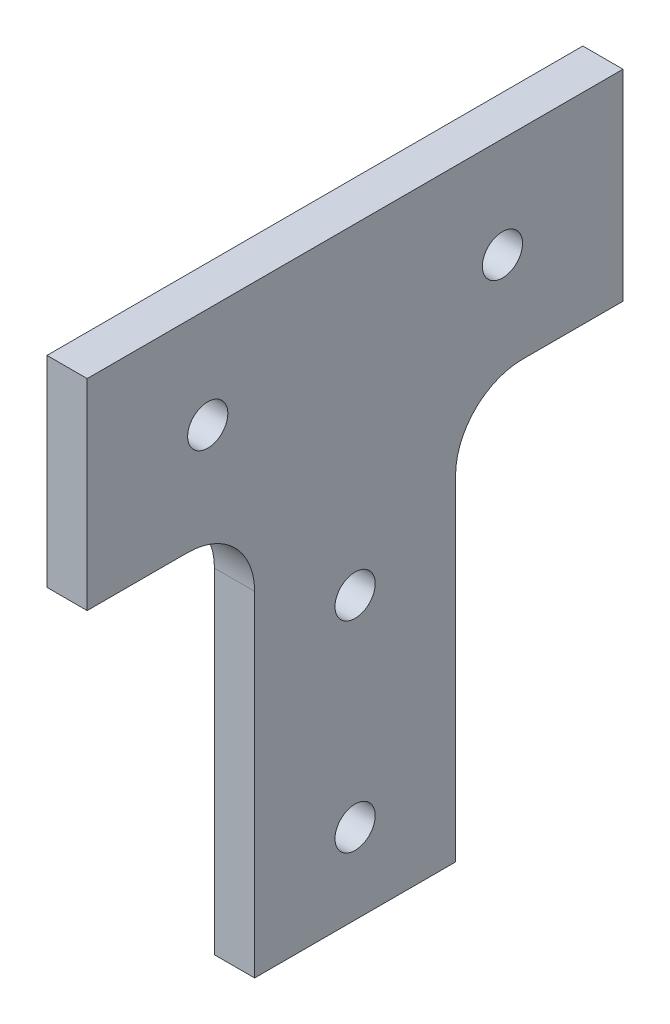
SolidWorks part; units mm, degrees
ref_plane "前视基准面" through (0, 0, 0) normal (0, 0, 1) x (1, 0, 0)
ref_plane "上视基准面" through (0, 0, 0) normal (0, 1, 0) x (1, 0, 0)
ref_plane "右视基准面" through (0, 0, 0) normal (1, 0, 0) x (0, 0, -1)
sketch "草图1" plane through (0, 0, 0) normal (1, 0, 0) x (0, 0, -1)
  line L0 (0, 0) -> (40, 0)
  line L1 (40, 0) -> (40, -15)
  line L2 (40, -15) -> (32.5, -15)
  line L3 (27.5, -20) -> (27.5, -45)
  line L4 (27.5, -45) -> (12.5, -45)
  line L5 (12.5, -45) -> (12.5, -20)
  line L6 (7.5, -15) -> (0, -15)
  line L7 (0, -15) -> (0, 0)
  arc A0 (32.5, -15) -> (27.5, -20) centre (32.5, -20) ccw
  arc A1 (12.5, -20) -> (7.5, -15) centre (7.5, -20) ccw
  point P11 (27.5, -15)
  dimension "D7" = 5
  dimension "D1" = 15
  dimension "D2" = 15
  dimension "D3" = 15
  dimension "D4" = 40
  dimension "D5" = 12.5
  dimension "D6" = 30
extrude "凸台-拉伸1" add sketch "草图1" along normal blind 3
sketch "草图2" plane through (3, 0, 0) normal (1, 0, 0) x (0, 0, -1)
  line L0 (40, -15) -> (40, 0) construction
  line L1 (0, 0) -> (0, -15) construction
  line L2 (12.5, -45) -> (27.5, -45) construction
  circle A0 centre (31, -7.5) radius 1.5
  circle A1 centre (9, -7.5) radius 1.5
  circle A2 centre (20, -39) radius 1.5
  circle A3 centre (20, -24) radius 1.5
  point P14 (0, 0)
  point P15 (0, -7.5)
  point P16 (20, -45)
  dimension "D1" = 3
  dimension "D2" = 9
  dimension "D3" = 9
  dimension "D4" = 6
  dimension "D5" = 15
extrude "切除-拉伸1" cut sketch "草图2" against normal blind 3
